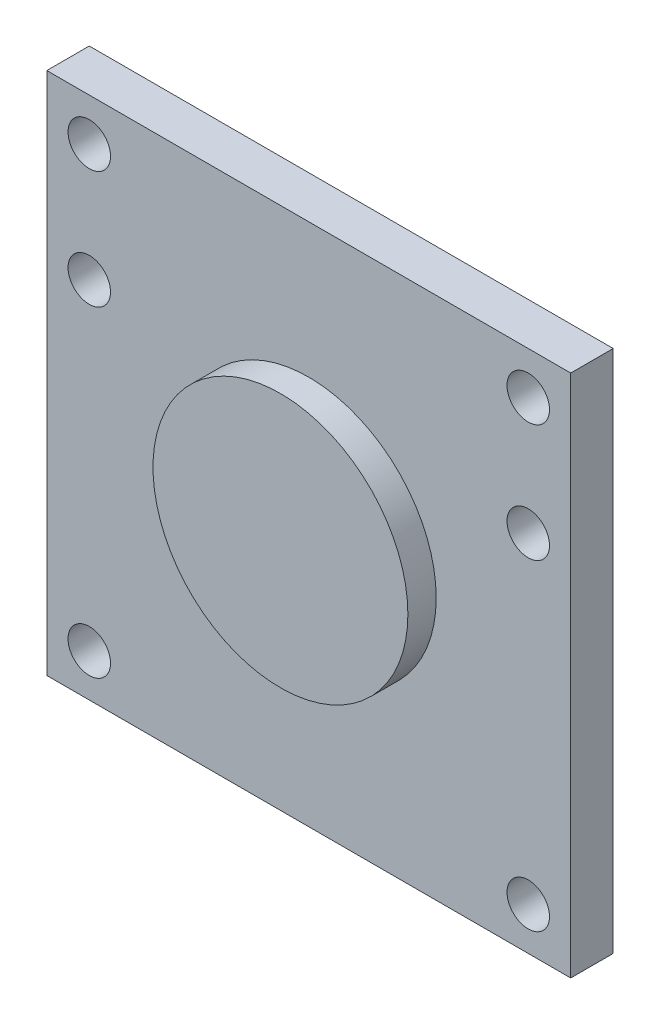
SolidWorks part; units mm, degrees
ref_plane "Front Plane" through (0, 0, 0) normal (0, 0, 1) x (1, 0, 0)
ref_plane "Top Plane" through (0, 0, 0) normal (0, 1, 0) x (1, 0, 0)
ref_plane "Right Plane" through (0, 0, 0) normal (1, 0, 0) x (0, 0, -1)
sketch "Sketch1" plane through (0, 0, 0) normal (0, 0, 1) x (1, 0, 0)
  line L0 (-15.5, 7.2) -> (15.5, 7.2) construction
  line L1 (-18.5, 18.5) -> (18.5, 18.5)
  line L2 (-18.5, 18.5) -> (-18.5, -18.5)
  line L3 (-18.5, -18.5) -> (18.5, -18.5)
  line L4 (18.5, 18.5) -> (18.5, -18.5)
  line L5 (-18.5, 18.5) -> (18.5, -18.5) construction
  line L6 (-18.5, -18.5) -> (18.5, 18.5) construction
  line L7 (-15.5, 15.5) -> (15.5, 15.5) construction
  line L8 (-15.5, 15.5) -> (-15.5, -15.5) construction
  line L9 (-15.5, -15.5) -> (15.5, -15.5) construction
  line L10 (15.5, 15.5) -> (15.5, -15.5) construction
  line L11 (-15.5, 15.5) -> (15.5, -15.5) construction
  line L12 (-15.5, -15.5) -> (15.5, 15.5) construction
  circle A0 centre (15.5, 7.2) radius 1.5
  circle A1 centre (-15.5, 7.2) radius 1.5
  circle A2 centre (-15.5, 15.5) radius 1.5
  circle A3 centre (15.5, 15.5) radius 1.5
  circle A4 centre (15.5, -15.5) radius 1.5
  circle A5 centre (-15.5, -15.5) radius 1.5
  point P0 (0, 0)
  point P6 (0, 0)
  dimension "D6" = 3
  dimension "D1" = 37
  dimension "D2" = 37
  dimension "D3" = 31
  dimension "D4" = 31
  dimension "D5" = 7.2
extrude "Boss-Extrude1" add sketch "Sketch1" along normal blind 3
sketch "Sketch2" plane through (0, 0, 3) normal (0, 0, 1) x (1, 0, 0)
  circle A0 centre (0, 0) radius 9
  dimension "D1" = 18
extrude "Boss-Extrude2" add sketch "Sketch2" along normal blind 2
